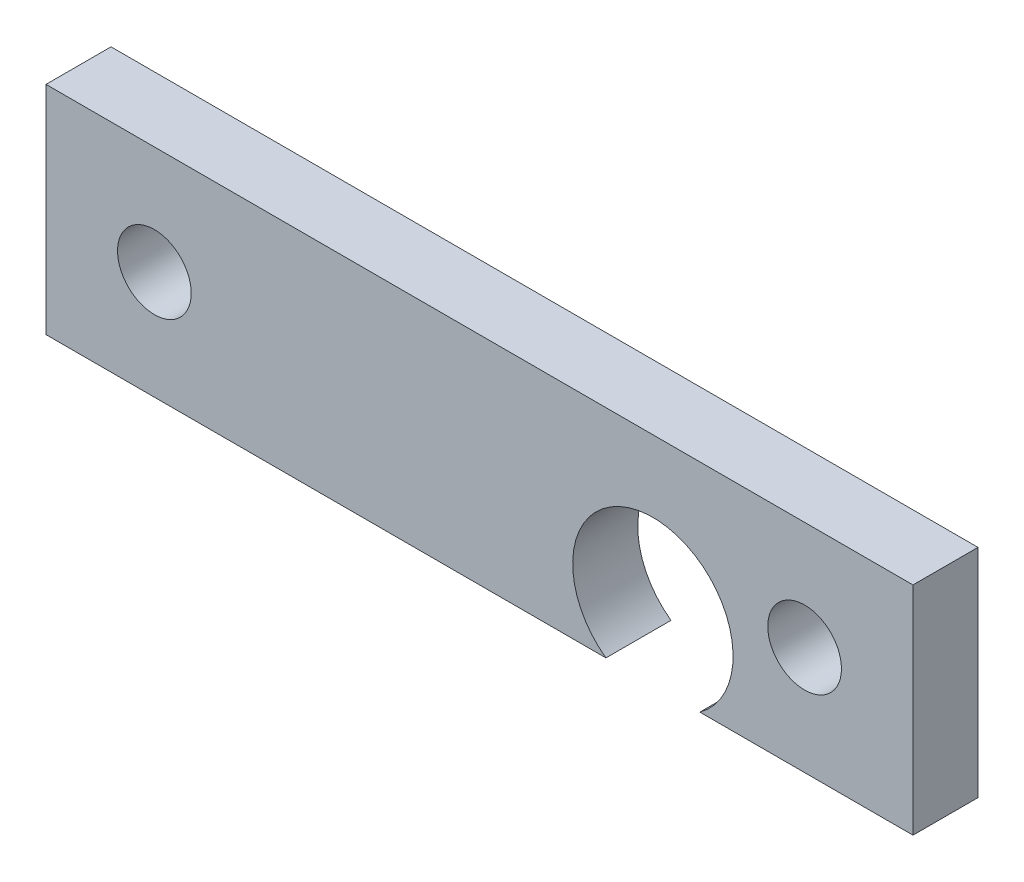
SolidWorks part; units mm, degrees
other "Platform Joint Strap 1 Left"
ref_plane "Front Plane" through (0, 0, 0) normal (0, 0, 1) x (1, 0, 0)
ref_plane "Top Plane" through (0, 0, 0) normal (0, 1, 0) x (1, 0, 0)
ref_plane "Right Plane" through (0, 0, 0) normal (1, 0, 0) x (0, 0, -1)
sketch3d "Main Profile Sketch datum points"
  point P0 (0, 0, 44.5)
  point P1 (10, 0, 44.5)
  point P2 (0, 10, 44.5)
ref_plane "Main Profile Sketch plane" through (0, 0, 44.5) normal (0, 0, 1) x (1, 0, 0)
sketch "Main Profile Sketch" plane through (0, 0, 44.5) normal (0, 0, 1) x (1, 0, 0)
  line L0 (-130, 41.5) -> (-90, 41.5)
  line L1 (-90, 41.5) -> (-90, 31.5)
  line L2 (-99.8344, 31.5) -> (-90, 31.5)
  line L3 (-130, 31.5) -> (-104.1656, 31.5)
  line L4 (-130, 41.5) -> (-130, 31.5)
  arc A0 (-99.8344, 31.5) -> (-104.1656, 31.5) centre (-102, 34.5) ccw
  circle A1 centre (-125, 36.5) radius 1.7
  circle A2 centre (-95, 36.5) radius 1.7
extrude "Main Extrusion" add sketch "Main Profile Sketch" against normal blind 3 separate body
